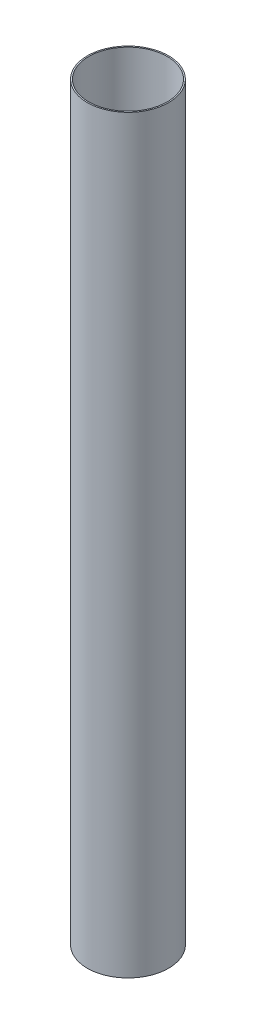
SolidWorks part; units mm, degrees
ref_plane "Front Plane" through (0, 0, 0) normal (0, 0, 1) x (1, 0, 0)
ref_plane "Top Plane" through (0, 0, 0) normal (0, 1, 0) x (1, 0, 0)
ref_plane "Right Plane" through (0, 0, 0) normal (1, 0, 0) x (0, 0, -1)
sketch "Sketch1" plane through (0, 0, 0) normal (0, 1, 0) x (1, 0, 0)
  circle A0 centre (0, 0) radius 0.76
  circle A1 centre (0, 0) radius 0.735
extrude "Boss-Extrude1" add sketch "Sketch1" along normal blind 14.02
